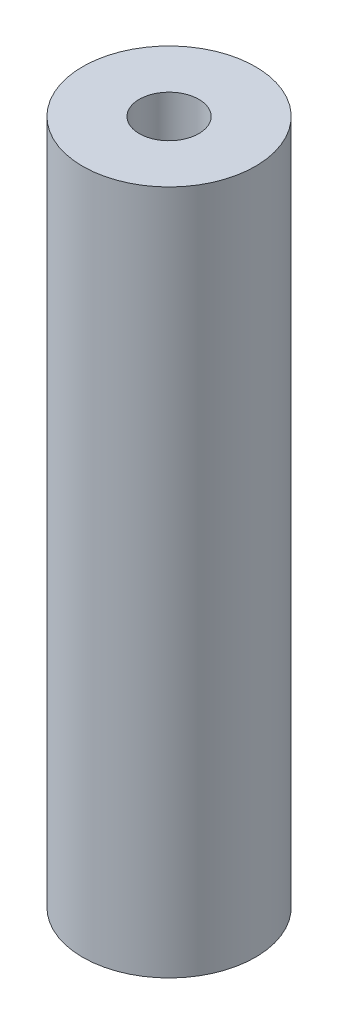
SolidWorks part; units mm, degrees
ref_plane "Front Plane" through (0, 0, 0) normal (0, 0, 1) x (1, 0, 0)
ref_plane "Top Plane" through (0, 0, 0) normal (0, 1, 0) x (1, 0, 0)
ref_plane "Right Plane" through (0, 0, 0) normal (1, 0, 0) x (0, 0, -1)
sketch "Sketch1" plane through (0, 0, 0) normal (0, 1, 0) x (1, 0, 0)
  circle A0 centre (0, 0) radius 12.7
  circle A1 centre (0, 0) radius 36.83
  dimension "D1" = 73.66
  dimension "D2" = 25.4
extrude "Boss-Extrude1" add sketch "Sketch1" along normal blind 292.1
